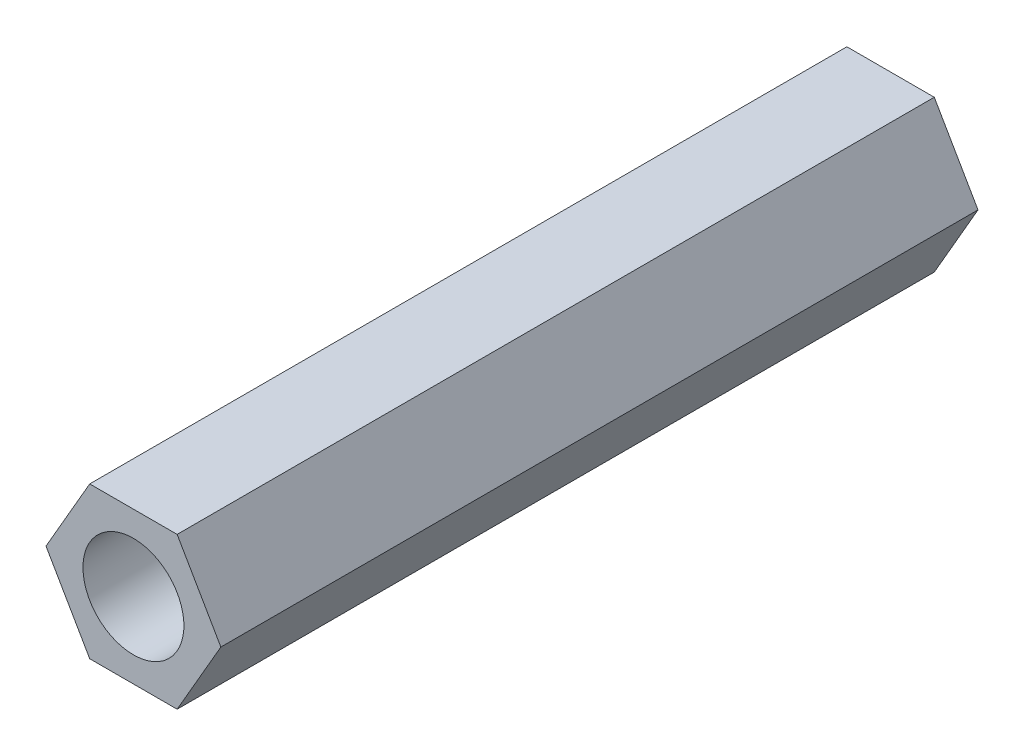
SolidWorks part; units mm, degrees
ref_plane "前视基准面" through (0, 0, 0) normal (0, 0, 1) x (1, 0, 0)
ref_plane "上视基准面" through (0, 0, 0) normal (0, 1, 0) x (1, 0, 0)
ref_plane "右视基准面" through (0, 0, 0) normal (1, 0, 0) x (0, 0, -1)
other "Configuration Table"
ref_plane "基准面1" through (0, 0, 0) normal (0, 0, -1) x (-1, 0, 0)
sketch "草图1" plane through (0, 0, 0) normal (0, 0, -1) x (-1, 0, 0)
  line L0 (3.4641, -6) -> (6.9282, 0)
  line L1 (6.9282, 0) -> (3.4641, 6)
  line L2 (3.4641, 6) -> (-3.4641, 6)
  line L3 (-3.4641, 6) -> (-6.9282, 0)
  line L4 (-6.9282, 0) -> (-3.4641, -6)
  line L5 (-3.4641, -6) -> (3.4641, -6)
  circle A0 centre (0, 0) radius 4
  dimension "D1" = 8
  dimension "D2" = 3.4641
  dimension "D3" = 6.9282
  dimension "D4" = 10.3923
  dimension "D5" = 13.8564
  dimension "D6" = 6
  dimension "D7" = 12
extrude "凸台-拉伸1" add sketch "草图1" against normal blind 60
